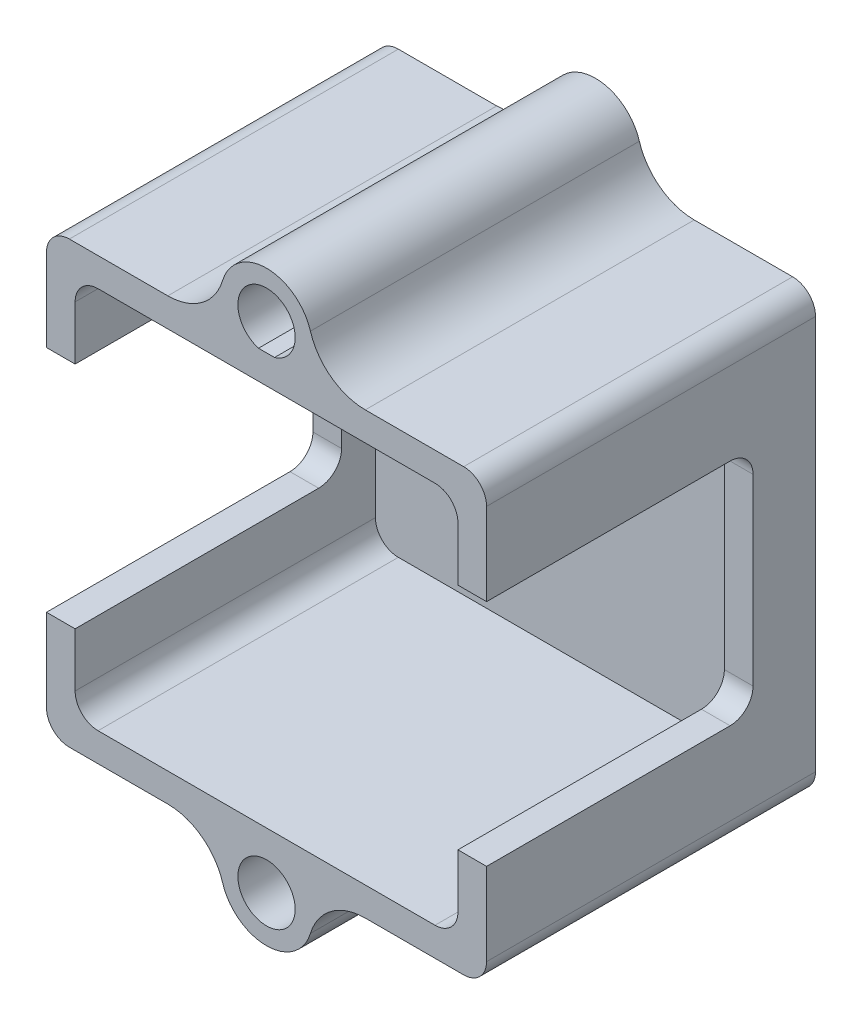
SolidWorks part; units mm, degrees
ref_plane "Front Plane" through (0, 0, 0) normal (0, 0, 1) x (1, 0, 0)
ref_plane "Top Plane" through (0, 0, 0) normal (0, 1, 0) x (1, 0, 0)
ref_plane "Right Plane" through (0, 0, 0) normal (1, 0, 0) x (0, 0, -1)
sketch "Sketch1" plane through (0, 0, 0) normal (0, 0, 1) x (1, 0, 0)
  line L1 (21.209, 21.209) -> (-21.209, 21.209)
  line L2 (21.209, 21.209) -> (21.209, -21.209)
  line L3 (21.209, -21.209) -> (-21.209, -21.209)
  line L4 (-21.209, 21.209) -> (-21.209, -21.209)
  line L5 (21.209, 21.209) -> (-21.209, -21.209) construction
  line L6 (21.209, -21.209) -> (-21.209, 21.209) construction
  line L7 (24.384, -24.384) -> (-24.384, -24.384)
  line L8 (24.384, -24.384) -> (24.384, 24.384)
  line L9 (24.384, 24.384) -> (-24.384, 24.384)
  line L10 (-24.384, -24.384) -> (-24.384, 24.384)
  line L11 (24.384, -24.384) -> (-24.384, 24.384) construction
  line L12 (24.384, 24.384) -> (-24.384, -24.384) construction
  circle A0 centre (0, 27.432) radius 3.175
  circle A1 centre (0, -27.432) radius 3.175
  circle A2 centre (0, 27.432) radius 5.08
  circle A3 centre (0, -27.432) radius 5.08
  point P4 (0, 0)
  point P10 (0, 0)
  dimension "D5" = 6.35
  dimension "D8" = 10.16
  dimension "D1" = 27.432
  dimension "D2" = 27.432
  dimension "D3" = 42.418
  dimension "D4" = 42.418
  dimension "D6" = 3.175
  dimension "D7" = 3.175
extrude "Boss-Extrude1" add sketch "Sketch1" along normal blind 36.449 contours A3 L3 L4 L1 A2 L9 L10 L7 | A3 L7 L8 L9 A2 L1 L2 L3 | L9 A2 L1 | L9 A2 A0 | L7 A3 A1 | L7 A3 L3
sketch "Sketch2" plane through (-21.209, 0, 0) normal (1, 0, 0) x (0, 0, -1)
  line L0 (-36.449, -21.209) -> (0, -21.209) construction
  line L1 (0, 21.209) -> (-3.175, 21.209)
  line L2 (0, 21.209) -> (0, -21.209)
  line L3 (0, -21.209) -> (-3.175, -21.209)
  line L4 (-3.175, 21.209) -> (-3.175, -21.209)
  dimension "D1" = 3.175
extrude "Boss-Extrude2" add sketch "Sketch2" along normal up to next
sketch "Sketch3" plane through (0, 0, 0) normal (0, 0, -1) x (-1, 0, 0)
  circle A0 centre (0, 27.432) radius 5.08
  circle A1 centre (0, -27.432) radius 5.08
extrude "Cut-Extrude1" [suppressed] cut sketch "Sketch3" against normal blind 25.4
sketch "Sketch4" plane through (24.384, 0, 0) normal (1, 0, 0) x (0, 0, -1)
  line L0 (-36.449, -24.384) -> (-36.449, 24.384) construction
  line L1 (-6.9259, 12.7) -> (-36.449, 12.7)
  line L2 (-6.9259, 12.7) -> (-6.9259, -12.7)
  line L3 (-6.9259, -12.7) -> (-36.449, -12.7)
  line L4 (-36.449, 12.7) -> (-36.449, -12.7)
  line L6 (0, -24.384) -> (0, 24.384) construction
  point P6 (0, 0)
  point P9 (-6.9259, 0)
  dimension "D1" = 25.4
extrude "Cut-Extrude2" cut sketch "Sketch4" against normal through all
fillet "Fillet1" radius 2.54 12 edges at (21.209, -21.209, 19.812) (21.209, 21.209, 19.812) (-21.209, 21.209, 19.812) (-21.209, -21.209, 19.812) (-24.384, 24.384, 18.2245) (-24.384, -24.384, 18.2245) (24.384, -24.384, 18.2245) (24.384, 24.384, 18.2245) (-22.7965, 12.7, 6.9259) (-22.7965, -12.7, 6.9259) (22.7965, -12.7, 6.9259) (22.7965, 12.7, 6.9259)
fillet "Fillet2" radius 6.35 4 edges at (4.064, -24.384, 18.2245) (-4.064, -24.384, 18.2245) (-4.064, 24.384, 18.2245) (4.064, 24.384, 18.2245)
